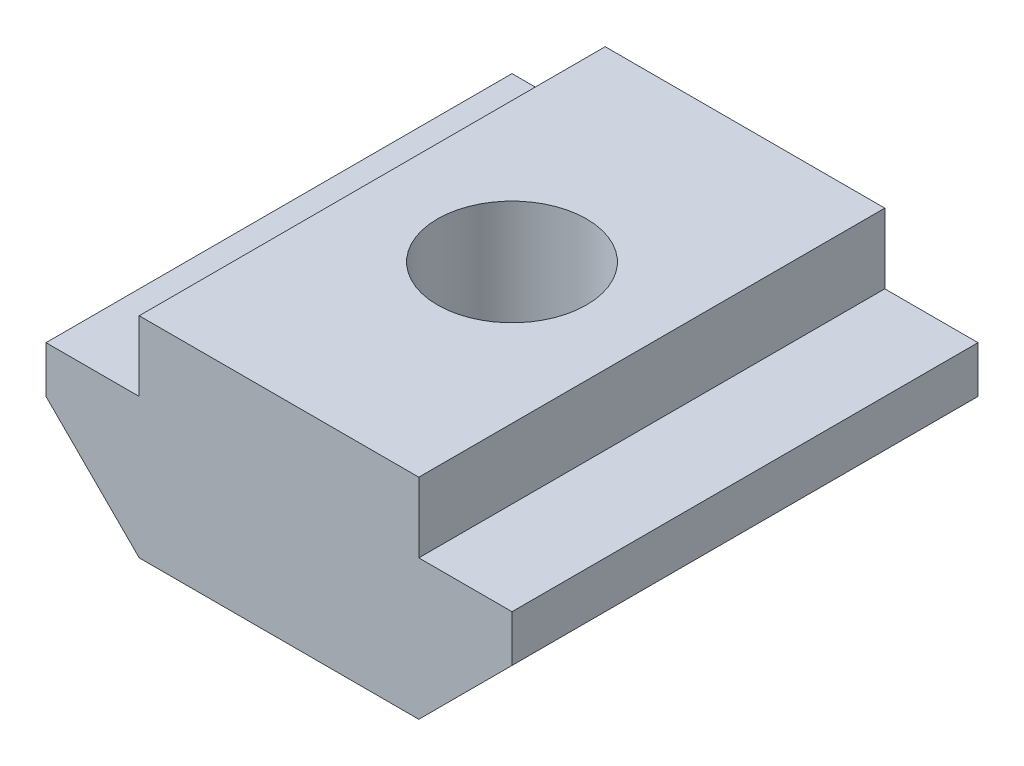
SolidWorks part; units mm, degrees
material "锌合金 7; AG40B; Zn-4Al-0.015Mg"
ref_plane "前视基准面" through (0, 0, 0) normal (0, 0, 1) x (1, 0, 0)
ref_plane "上视基准面" through (0, 0, 0) normal (0, 1, 0) x (1, 0, 0)
ref_plane "右视基准面" through (0, 0, 0) normal (1, 0, 0) x (0, 0, -1)
sketch "草图1" plane through (0, 0, 0) normal (0, 0, 1) x (1, 0, 0)
  line L1 (-5, 1.5) -> (5, 1.5)
  line L2 (-5, 1.5) -> (-5, -1.5)
  line L3 (-5, -1.5) -> (5, -1.5)
  line L4 (5, 1.5) -> (5, -1.5)
  line L5 (-5, 1.5) -> (5, -1.5) construction
  line L6 (-5, -1.5) -> (5, 1.5) construction
  line L7 (-3, 3) -> (3, 3)
  line L8 (-3, 3) -> (-3, 0)
  line L9 (-3, 0) -> (3, 0)
  line L10 (3, 3) -> (3, 0)
  line L11 (-3, 3) -> (3, 0) construction
  line L12 (-3, 0) -> (3, 3) construction
  point P0 (0, 0)
  point P5 (0, 1.5)
  dimension "D1" = 10
  dimension "D2" = 3
  dimension "D3" = 3
  dimension "D4" = 6
extrude "凸台-拉伸1" add sketch "草图1" along normal mid plane 10 contours L1 L4 L3 L2 | L7 L10 L9 L8
sketch "草图2" plane through (0, 3, 0) normal (0, 1, 0) x (1, 0, 0)
  circle A0 centre (0, 0) radius 1.6
  dimension "D1" = 3.2
extrude "切除-拉伸1" cut sketch "草图2" against normal blind 10
cosmetic thread "装饰螺纹线1" parameters "D2"=4
chamfer "倒角1" distance 2 angle 45 2 edges at (-5, -1.5, 0) (5, -1.5, 0)
